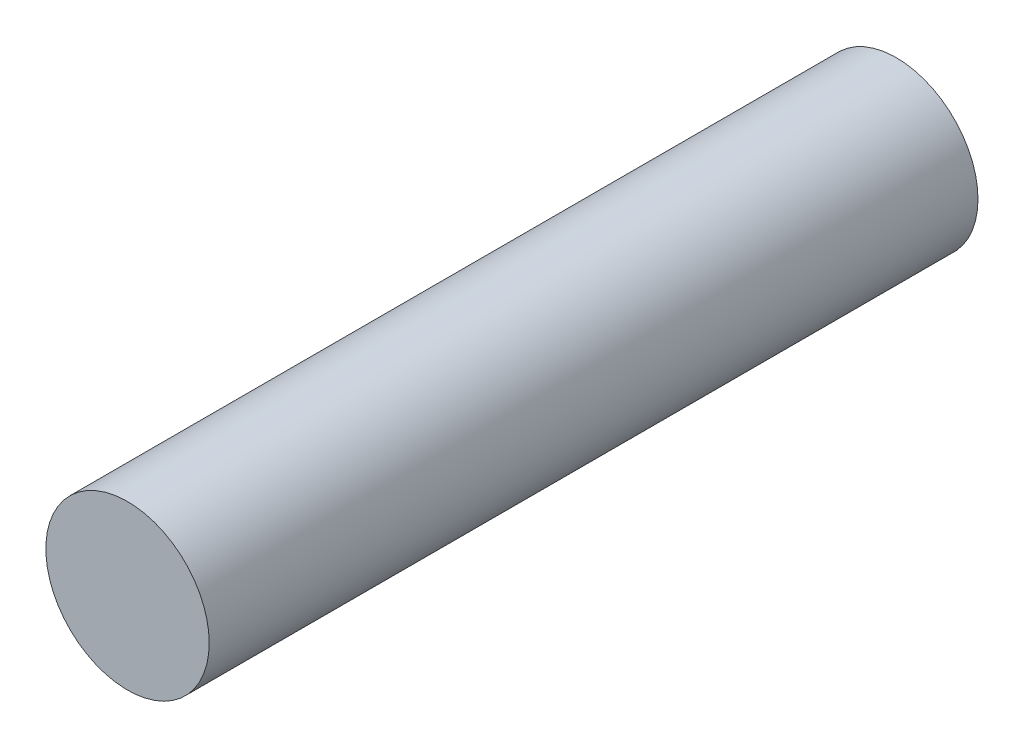
SolidWorks part; units mm, degrees
ref_plane "前视基准面" through (0, 0, 0) normal (0, 0, 1) x (1, 0, 0)
ref_plane "上视基准面" through (0, 0, 0) normal (0, 1, 0) x (1, 0, 0)
ref_plane "右视基准面" through (0, 0, 0) normal (1, 0, 0) x (0, 0, -1)
sketch "草图1" plane through (0, 0, 0) normal (0, 0, 1) x (1, 0, 0)
  circle A0 centre (0, 0) radius 1.7
  dimension "D1" = 3.4
extrude "拉伸1" add sketch "草图1" along normal blind 16
